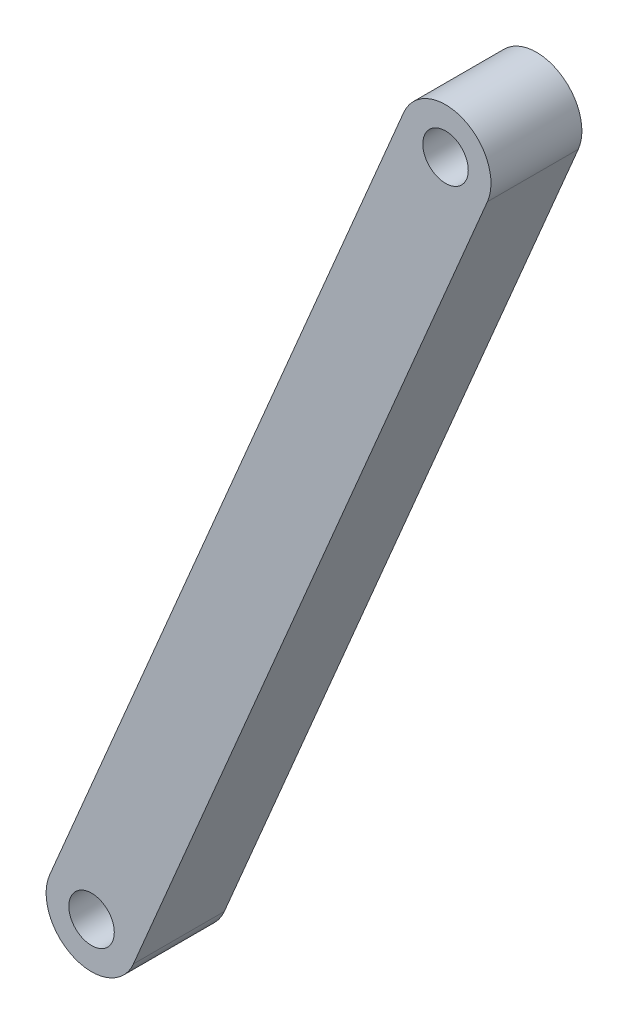
SolidWorks part; units mm, degrees
ref_plane "前视基准面" through (0, 0, 0) normal (0, 0, 1) x (1, 0, 0)
ref_plane "上视基准面" through (0, 0, 0) normal (0, 1, 0) x (1, 0, 0)
ref_plane "右视基准面" through (0, 0, 0) normal (1, 0, 0) x (0, 0, -1)
sketch "草图1" plane through (0, 0, 0) normal (0, 0, 1) x (1, 0, 0)
  line L0 (39.0529, 25) -> (78.0004, 117.1037) construction
  line L1 (34.4477, 26.9474) -> (73.3952, 119.0511)
  line L2 (43.658, 23.0526) -> (82.6056, 115.1563)
  arc A0 (34.4477, 26.9474) -> (43.658, 23.0526) centre (39.0529, 25) ccw
  arc A1 (82.6056, 115.1563) -> (73.3952, 119.0511) centre (78.0004, 117.1037) ccw
  circle A2 centre (78.0004, 117.1037) radius 2.5
  circle A3 centre (39.0529, 25) radius 2.5
  point P4 (58.5266, 71.0518)
  dimension "D1" = 10
extrude "凸台-拉伸1" add sketch "草图1" along normal mid plane 10
